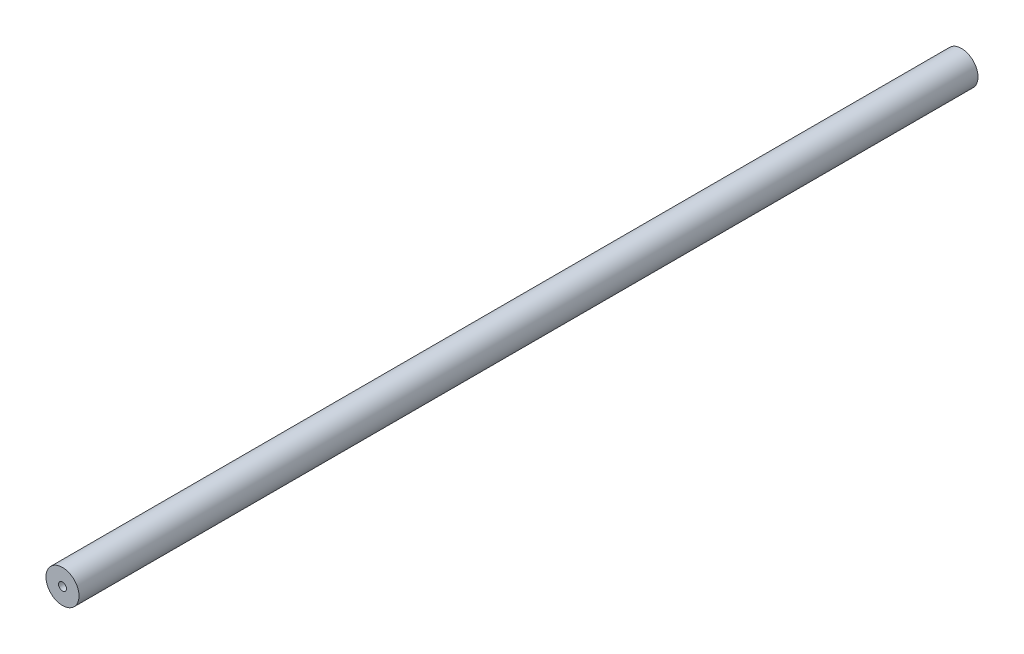
SolidWorks part; units mm, degrees
material "0.6010 (EN-GJL-100)"
ref_plane "Ön Düzlem" through (0, 0, 0) normal (0, 0, 1) x (1, 0, 0)
ref_plane "Üst Düzlem" through (0, 0, 0) normal (0, 1, 0) x (1, 0, 0)
ref_plane "Sağ Düzlem" through (0, 0, 0) normal (1, 0, 0) x (0, 0, -1)
sketch "Çizim1" plane through (0, 0, 0) normal (0, 0, 1) x (1, 0, 0)
  circle A0 centre (0, 0) radius 12.5
  circle A1 centre (0, 0) radius 3
  dimension "D1" = 25
  dimension "D2" = 6
extrude "Yükseklik-Ekstrüzyon1" add sketch "Çizim1" along normal blind 680
